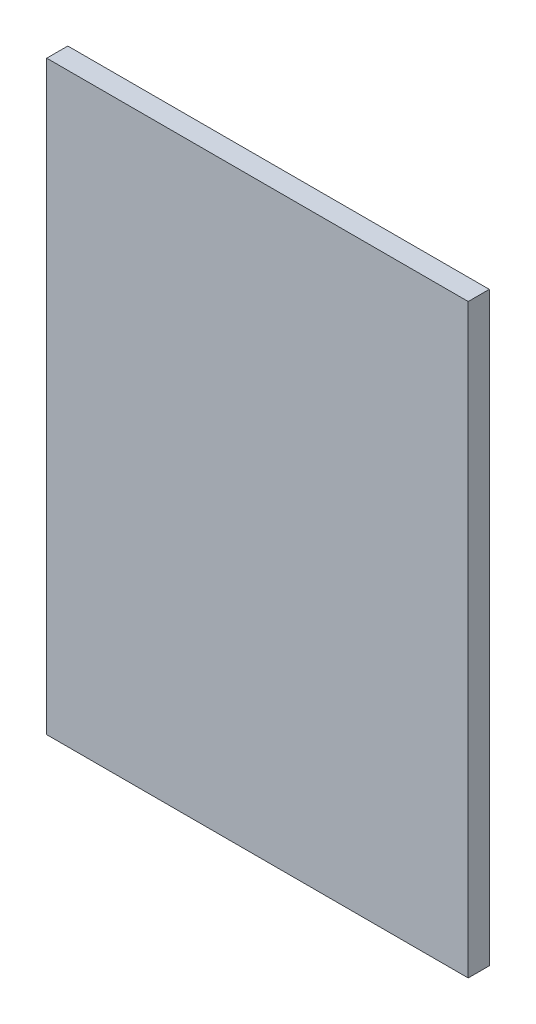
SolidWorks part; units mm, degrees
ref_plane "Plano frontal" through (0, 0, 0) normal (0, 0, 1) x (1, 0, 0)
ref_plane "Plano superior" through (0, 0, 0) normal (0, 1, 0) x (1, 0, 0)
ref_plane "Plano direito" through (0, 0, 0) normal (1, 0, 0) x (0, 0, -1)
sketch "Esboço1" plane through (0, 0, 0) normal (0, 0, 1) x (1, 0, 0)
  line L1 (-62.5, 87.5) -> (62.5, 87.5)
  line L2 (-62.5, 87.5) -> (-62.5, -87.5)
  line L3 (-62.5, -87.5) -> (62.5, -87.5)
  line L4 (62.5, 87.5) -> (62.5, -87.5)
  line L5 (-62.5, 87.5) -> (62.5, -87.5) construction
  line L6 (-62.5, -87.5) -> (62.5, 87.5) construction
  point P0 (0, 0)
  dimension "D1" = 125
  dimension "D2" = 175
extrude "Ressalto-extrusão1" add sketch "Esboço1" along normal blind 5
sketch "Esboço2" plane through (0, 0, 0) normal (0, 0, -1) x (-1, 0, 0)
  line L1 (9, 24.5) -> (9, -24.5)
  line L3 (46.5, 24.5) -> (46.5, -24.5)
  line L4 (46.5, -24.5) -> (44, -24.5)
  line L5 (44, -24.5) -> (44, 24.5)
  line L6 (44, 24.5) -> (46.5, 24.5)
  line L10 (9, -24.5) -> (6.5, -24.5)
  line L11 (6.5, -24.5) -> (6.5, 24.5)
  line L12 (6.5, 24.5) -> (9, 24.5)
extrude "Ressalto-extrusão2" add sketch "Esboço2" along normal blind 5.4
sketch "Esboço3" plane through (-46.5, 0, 0) normal (-1, 0, 0) x (0, 0, 1)
  line L0 (-5.4, -24.5) -> (0, -24.5) construction
  line L1 (-5.4, 24.5) -> (0, 24.5) construction
  line L2 (-5.4, -24.5) -> (-5.4, 24.5) construction
  line L3 (0, -24.5) -> (0, 24.5) construction
  circle A0 centre (-2.7, -21.9) radius 1.35
  circle A1 centre (-2.7, 21.9) radius 1.35
  circle A2 centre (-2.7, 0) radius 1.35
  dimension "D1" = 2.6
  dimension "D2" = 2.6
  dimension "D3" = 2.7
  dimension "D4" = 2.7
  dimension "D5" = 2.7
  dimension "D6" = 2.7
  dimension "D7" = 2.7
  dimension "D8" = 2.7
  dimension "D9" = 24.5
fillet "Filete1" radius 2 4 edges at (-7.75, -24.5, -5.4) (-45.25, -24.5, -5.4) (-7.75, 24.5, -5.4) (-45.25, 24.5, -5.4)
extrude "Corte-extrusão2" cut sketch "Esboço3" against normal through all
sketch "Esboço4" plane through (0, 0, 0) normal (0, 0, -1) x (-1, 0, 0)
  line L0 (62.5, -87.5) -> (62.5, -69.5)
  line L1 (62.5, 87.5) -> (62.5, -87.5) construction
  line L2 (62.5, 87.5) -> (62.5, 69.5)
  line L3 (62.5, -69.5) -> (-37.5, -69.5)
  line L4 (-37.5, -69.5) -> (-37.5, 69.5)
  line L5 (-37.5, 69.5) -> (62.5, 69.5)
  line L6 (62.5, -87.5) -> (-62.5, -87.5)
  line L7 (-62.5, -87.5) -> (-62.5, 87.5)
  line L8 (-62.5, 87.5) -> (62.5, 87.5)
extrude "Corte-extrusão3" cut sketch "Esboço4" against normal through all
